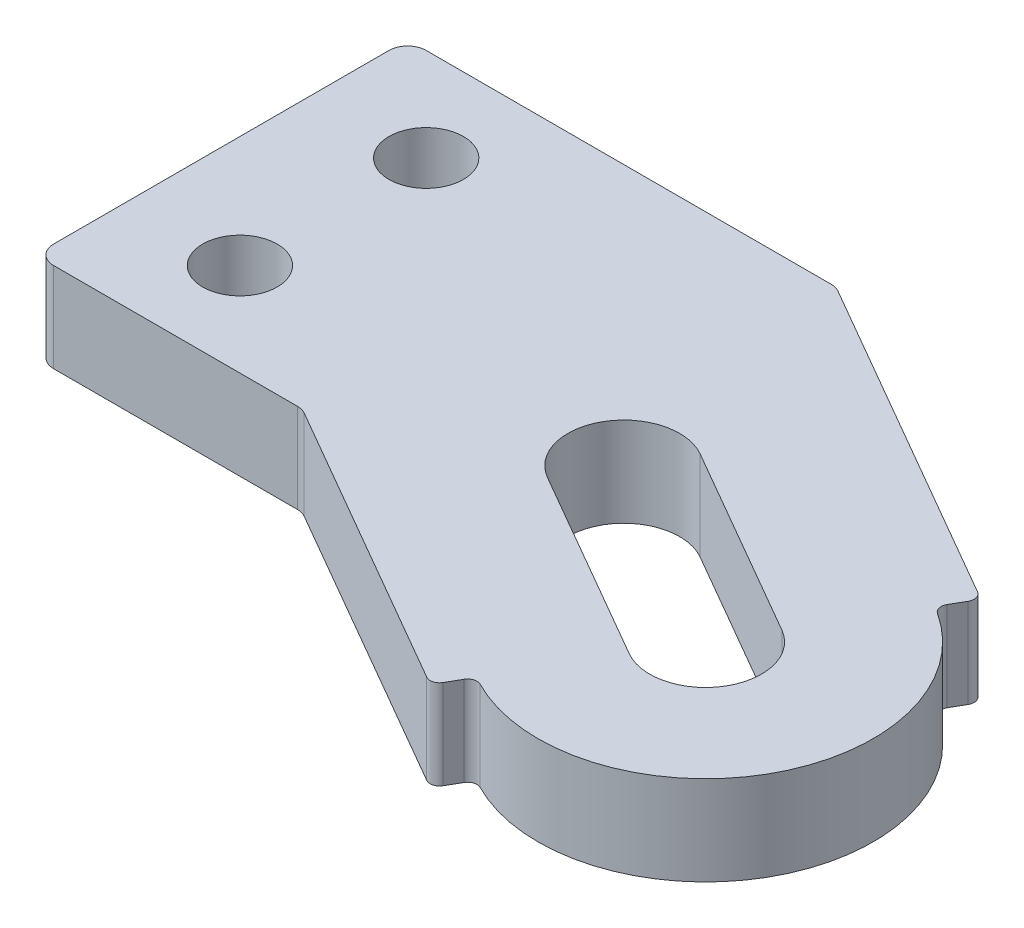
SolidWorks part; units mm, degrees
ref_plane "Front Plane" through (0, 0, 0) normal (0, 0, 1) x (1, 0, 0)
ref_plane "Top Plane" through (0, 0, 0) normal (0, 1, 0) x (1, 0, 0)
ref_plane "Right Plane" through (0, 0, 0) normal (1, 0, 0) x (0, 0, -1)
sketch "Sketch1" plane through (0, 0, 0) normal (0, 1, 0) x (1, 0, 0)
  line L0 (-21.6191, -25) -> (-14.1191, -25) construction
  line L2 (-21.6191, 0) -> (-21.6191, -25) construction
  line L5 (-14.1191, -25) -> (-14.1191, -18.75) construction
  line L6 (-21.6191, -12.5) -> (-17.6325, -12.5) construction
  line L7 (23.3809, -25) -> (33.895, -6.7891) construction
  line L8 (23.3809, -25) -> (13.8667, -41.4791) construction
  line L9 (29.3125, -14.7261) -> (29.8309, -13.8283)
  line L10 (25.2559, -21.7524) -> (12.2655, -14.2524)
  line L11 (21.5059, -28.2476) -> (8.5155, -20.7476)
  line L12 (17.4493, -35.2739) -> (16.9309, -36.1717)
  line L13 (16.0703, -36.4023) -> (-3.389, -25.1675)
  line L14 (29.6003, -12.9677) -> (7.4297, -0.1675)
  line L16 (-20.3691, 0) -> (6.8047, 0)
  line L17 (-21.6191, -1.25) -> (-21.6191, -23.75)
  line L18 (-20.3691, -25) -> (-4.014, -25)
  line L19 (23.3809, -20.6699) -> (23.3809, -25) construction
  circle A0 centre (-14.1191, -18.75) radius 2.5
  circle A1 centre (-14.1191, -6.25) radius 2.5
  arc A2 (21.5059, -28.2476) -> (25.2559, -21.7524) centre (23.3809, -25) ccw
  arc A3 (18.2805, -35.0274) -> (29.5147, -15.5692) centre (23.3809, -25) ccw
  arc A4 (12.2655, -14.2524) -> (8.5155, -20.7476) centre (10.3905, -17.5) ccw
  arc A5 (-3.389, -25.1675) -> (-4.014, -25) centre (-4.014, -26.25) ccw
  arc A6 (6.8047, 0) -> (7.4297, -0.1675) centre (6.8047, -1.25) cw
  arc A7 (16.9309, -36.1717) -> (16.0703, -36.4023) centre (16.3853, -35.8567) cw
  arc A8 (18.2805, -35.0274) -> (17.4493, -35.2739) centre (17.9949, -35.5889) ccw
  arc A9 (29.5147, -15.5692) -> (29.3125, -14.7261) centre (29.8581, -15.0411) cw
  arc A10 (29.6003, -12.9677) -> (29.8309, -13.8283) centre (29.2853, -13.5133) cw
  arc A11 (-21.6191, -23.75) -> (-20.3691, -25) centre (-20.3691, -23.75) ccw
  arc A12 (-20.3691, 0) -> (-21.6191, -1.25) centre (-20.3691, -1.25) ccw
  point P27 (-3.6791, -25)
  point P29 (-3.6791, -25)
  point P33 (16.6159, -36.7173)
  point P36 (17.7559, -34.7428)
  point P39 (29.0059, -15.2572)
  point P42 (30.1459, -13.2827)
  dimension "D6" = 5
  dimension "D8" = 7.5
  dimension "D9" = 22.5
  dimension "D16" = 2.28
  dimension "D18" = 25
  dimension "D21" = 1.25
  dimension "D22" = 1.25
  dimension "D23" = 0.63
  dimension "D24" = 1.25
  dimension "D2" = 25
  dimension "D3" = 21.6191
  dimension "D4" = 7.5
  dimension "D5" = 6.25
  dimension "D7" = 14.1191
  dimension "D10" = 23.3809
  dimension "D11" = 2.28
  dimension "D12" = 90
  dimension "D13" = 90
  dimension "D14" = 15
  dimension "D15" = 15
  dimension "D17" = 25
  dimension "D19" = 17.5
  dimension "D20" = 90
extrude "Boss-Extrude1" add sketch "Sketch1" along normal blind 6
